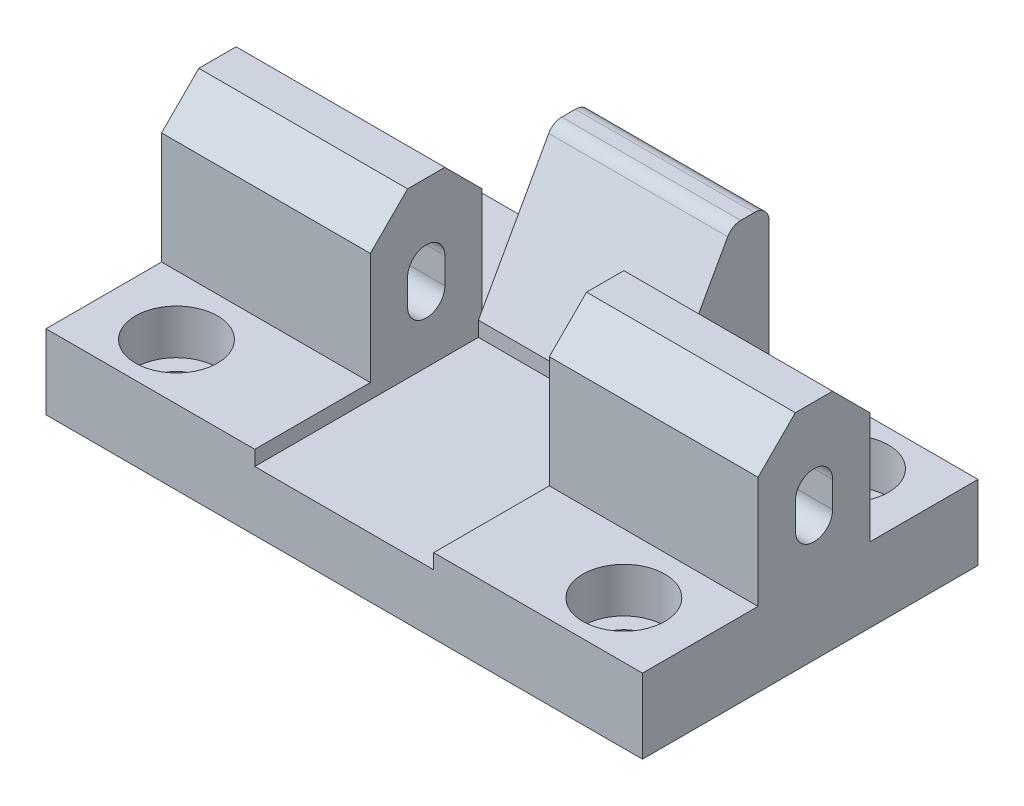
SolidWorks part; units mm, degrees
ref_plane "정면" through (0, 0, 0) normal (0, 0, 1) x (1, 0, 0)
ref_plane "윗면" through (0, 0, 0) normal (0, 1, 0) x (1, 0, 0)
ref_plane "우측면" through (0, 0, 0) normal (1, 0, 0) x (0, 0, -1)
sketch "스케치2" plane through (0, 0, 0) normal (0, 1, 0) x (1, 0, 0)
  line L1 (-40, -22.5) -> (40, -22.5)
  line L2 (-40, -22.5) -> (-40, 22.5)
  line L3 (-40, 22.5) -> (40, 22.5)
  line L4 (40, -22.5) -> (40, 22.5)
  dimension "D1" = 80
  dimension "D2" = 45
  dimension "D3" = 40
  dimension "D4" = 22.5
extrude "보스-돌출1" add sketch "스케치2" along normal blind 10
sketch "스케치3" plane through (0, 0, 0) normal (1, 0, 0) x (0, 0, -1)
  line L0 (22.5, 10) -> (22.5, 28)
  line L1 (22.5, 28) -> (17.5, 28)
  line L2 (17.5, 28) -> (7.5, 10)
  line L3 (-22.5, 10) -> (22.5, 10) construction
  line L4 (7.5, 10) -> (22.5, 10)
  line L5 (-22.5, 0) -> (22.5, 0) construction
  line L6 (-22.5, 10) -> (-22.5, 0) construction
  dimension "D1" = 40
  dimension "D2" = 28
  dimension "D3" = 30
extrude "보스-돌출2" add sketch "스케치3" along normal mid plane 24
fillet "필렛1" radius 2 2 edges at (0, 28, -22.5) (0, 28, -17.5)
sketch "스케치4" plane through (0, 10, 0) normal (0, 1, 0) x (1, 0, 0)
  line L0 (-40, -22.5) -> (40, -22.5) construction
  line L1 (-12, 7.5) -> (12, 7.5)
  line L2 (-12, 7.5) -> (-12, -22.5)
  line L3 (-12, -22.5) -> (12, -22.5)
  line L4 (12, 7.5) -> (12, -22.5)
  dimension "D1" = 24
extrude "컷-돌출1" cut sketch "스케치4" against normal blind 2
sketch "스케치5" plane through (0, 10, 0) normal (0, 1, 0) x (1, 0, 0)
  line L0 (-40, 22.5) -> (-40, -22.5) construction
  line L1 (-40, 8) -> (-12, 8)
  line L2 (-40, 8) -> (-40, -7)
  line L3 (-40, -7) -> (-12, -7)
  line L4 (-12, 8) -> (-12, -7)
  line L5 (-12, 7.5) -> (-12, -22.5) construction
  line L6 (40, -22.5) -> (40, 22.5) construction
  line L7 (40, 8) -> (12, 8)
  line L8 (40, 8) -> (40, -7)
  line L9 (40, -7) -> (12, -7)
  line L10 (12, 8) -> (12, -7)
  line L11 (12, -22.5) -> (12, 7.5) construction
  line L14 (12, -22.5) -> (40, -22.5) construction
  dimension "D1" = 15
  dimension "D2" = 15.5
extrude "보스-돌출3" add sketch "스케치5" along normal blind 20
chamfer "모따기1" distance 5 angle 45 4 edges at (-26, 30, -8) (-26, 30, 7) (26, 30, -8) (26, 30, 7)
sketch "스케치6" plane through (40, 0, 0) normal (1, 0, 0) x (0, 0, -1)
  line L0 (0.5, 19.75) -> (0.5, 16.25) construction
  line L1 (3, 19.75) -> (3, 16.25)
  line L2 (-2, 19.75) -> (-2, 16.25)
  line L4 (-22.5, 10) -> (-22.5, 0) construction
  line L5 (-22.5, 0) -> (22.5, 0) construction
  arc A0 (3, 19.75) -> (-2, 19.75) centre (0.5, 19.75) ccw
  arc A1 (-2, 16.25) -> (3, 16.25) centre (0.5, 16.25) ccw
  point P3 (0.5, 18)
  dimension "D2" = 2.5
  dimension "D1" = 3.5
  dimension "D3" = 23
  dimension "D4" = 18
extrude "컷-돌출2" cut sketch "스케치6" against normal through all
sketch "스케치8" plane through (0, 10, 0) normal (0, 1, 0) x (1, 0, 0)
  line L0 (-40, -7) -> (-40, -22.5) construction
  line L1 (-40, -22.5) -> (-12, -22.5) construction
  circle A0 centre (-30, 15) radius 5.5
  circle A1 centre (-30, -15) radius 5.5
  circle A2 centre (30, -15) radius 5.5
  circle A3 centre (30, 15) radius 5.5
  dimension "D3" = 11
  dimension "D1" = 10
  dimension "D2" = 7.5
  dimension "D4" = 30
  dimension "D5" = 60
extrude "컷-돌출3" cut sketch "스케치8" against normal blind 6
sketch "스케치9" plane through (0, 4, 0) normal (0, 1, 0) x (1, 0, 0)
  circle A0 centre (-30, 15) radius 3.25
  circle A1 centre (30, 15) radius 3.25
  circle A2 centre (30, -15) radius 3.25
  circle A3 centre (-30, -15) radius 3.25
  dimension "D1" = 6.5
extrude "컷-돌출4" cut sketch "스케치9" against normal through all
